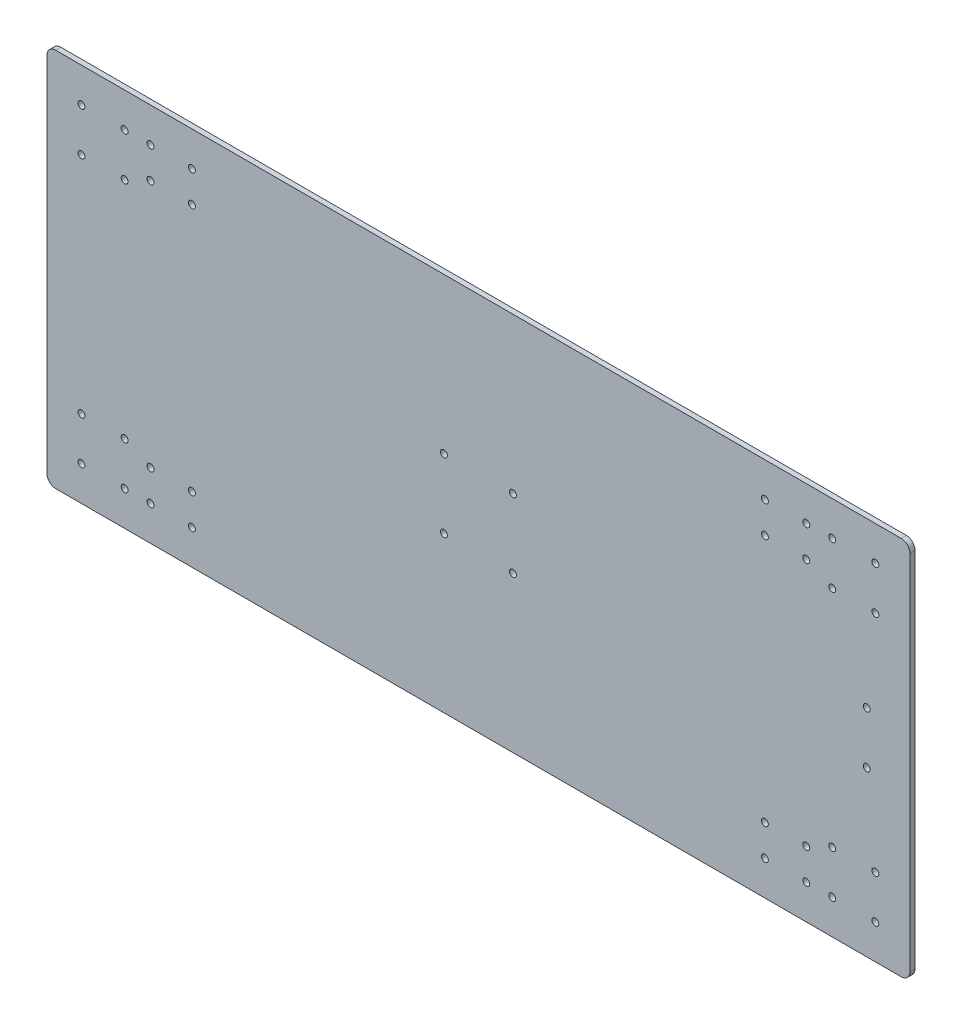
SolidWorks part; units mm, degrees
ref_plane "Płaszczyzna przednia" through (0, 0, 0) normal (0, 0, 1) x (1, 0, 0)
ref_plane "Płaszczyzna górna" through (0, 0, 0) normal (0, 1, 0) x (1, 0, 0)
ref_plane "Płaszczyzna prawa" through (0, 0, 0) normal (1, 0, 0) x (0, 0, -1)
sketch "Szkic1" plane through (0, 0, 0) normal (0, 0, 1) x (1, 0, 0)
  line L1 (-250, -110) -> (250, -110)
  line L2 (-250, -110) -> (-250, 110)
  line L3 (-250, 110) -> (250, 110)
  line L4 (250, -110) -> (250, 110)
  line L5 (-250, -110) -> (250, 110) construction
  line L6 (-250, 110) -> (250, -110) construction
  point P0 (0, 0)
  dimension "D1" = 220
  dimension "D2" = 500
extrude "Dodanie-wyciągnięcie1" add sketch "Szkic1" along normal blind 3
sketch "Szkic5" plane through (0, 0, 3) normal (0, 0, 1) x (1, 0, 0)
  circle A0 centre (225, 15) radius 2
  circle A1 centre (225, -15) radius 2
extrude "Wytnij-wyciągnięcie2" cut sketch "Szkic5" against normal up to next
sketch "Szkic7" plane through (0, 0, 3) normal (0, 0, 1) x (1, 0, 0)
  circle A0 centre (-20, 20) radius 2
  circle A1 centre (20, 20) radius 2
  circle A2 centre (20, -20) radius 2
  circle A3 centre (-20, -20) radius 2
  point P0 (0, 0)
extrude "Wytnij-wyciągnięcie4" cut sketch "Szkic7" against normal up to next
fillet "Zaokrąglenie1" radius 5 4 edges at (-250, -110, 1.5) (-250, 110, 1.5) (250, -110, 1.5) (250, 110, 1.5)
sketch "Szkic8" plane through (0, 0, 0) normal (0, 0, -1) x (-1, 0, 0)
  circle A0 centre (-230, -65) radius 2
  circle A1 centre (-205, -65) radius 2
  circle A2 centre (-205, -90) radius 2
  circle A3 centre (-230, -90) radius 2
extrude "Wytnij-wyciągnięcie5" cut sketch "Szkic8" against normal up to next
mirror "Lustro1" about plane through (0, 0, 0) normal (1, 0, 0) of "Wytnij-wyciągnięcie5"
mirror "Lustro2" about plane through (0, 0, 0) normal (0, 1, 0) of "Lustro1", "Wytnij-wyciągnięcie5"
sketch "Szkic9" plane through (0, 0, 0) normal (0, 0, -1) x (-1, 0, 0)
  circle A0 centre (-190, -72) radius 2
  circle A1 centre (-166, -72) radius 2
  circle A2 centre (-166, -90) radius 2
  circle A3 centre (-190, -90) radius 2
extrude "Wytnij-wyciągnięcie6" cut sketch "Szkic9" against normal up to next
mirror "Lustro3" about plane through (0, 0, 0) normal (0, 1, 0) of "Wytnij-wyciągnięcie6"
mirror "Lustro4" about plane through (0, 0, 0) normal (1, 0, 0) of "Lustro3", "Wytnij-wyciągnięcie6"
